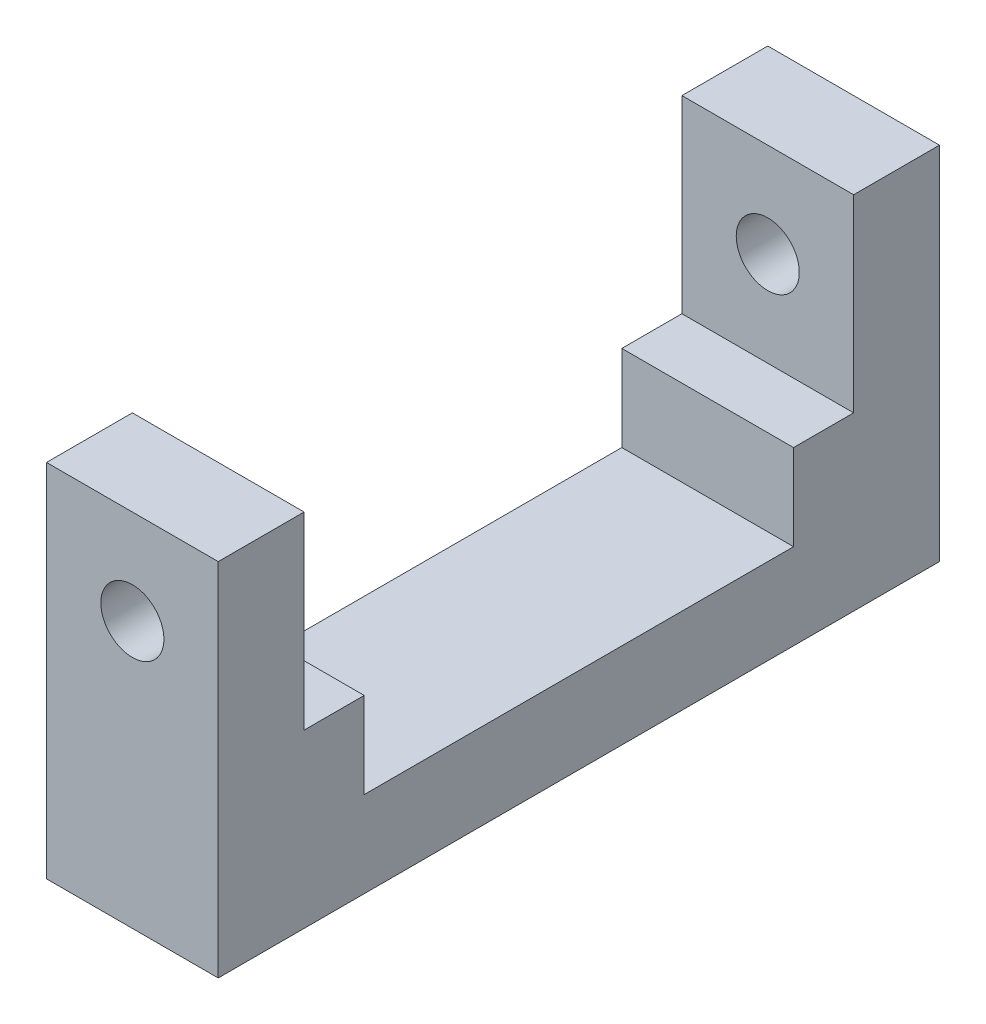
SolidWorks part; units mm, degrees
ref_plane "Front Plane" through (0, 0, 0) normal (0, 0, 1) x (1, 0, 0)
ref_plane "Top Plane" through (0, 0, 0) normal (0, 1, 0) x (1, 0, 0)
ref_plane "Right Plane" through (0, 0, 0) normal (1, 0, 0) x (0, 0, -1)
sketch "Sketch1" plane through (0, 0, 0) normal (1, 0, 0) x (0, 0, -1)
  line L1 (-21, -10.5) -> (21, -10.5)
  line L2 (-21, -10.5) -> (-21, 10.5)
  line L3 (-21, 10.5) -> (21, 10.5)
  line L4 (21, -10.5) -> (21, 10.5)
  line L5 (-21, -10.5) -> (21, 10.5) construction
  line L6 (-21, 10.5) -> (21, -10.5) construction
  line L7 (-16, 10.5) -> (16, 10.5)
  line L8 (-16, 10.5) -> (-16, -5.5)
  line L9 (-16, -5.5) -> (16, -5.5)
  line L10 (16, 10.5) -> (16, -5.5)
  line L11 (12.5, -5.5) -> (-12.5, -5.5)
  line L12 (12.5, -5.5) -> (12.5, -0.5)
  line L13 (12.5, -0.5) -> (-12.5, -0.5)
  line L14 (-12.5, -5.5) -> (-12.5, -0.5)
  line L15 (12.5, -5.5) -> (-12.5, -0.5) construction
  line L16 (12.5, -0.5) -> (-12.5, -5.5) construction
  line L21 (-16, -5.5) -> (-12.5, -5.5)
  line L22 (-16, -5.5) -> (-16, -0.5)
  line L23 (-16, -0.5) -> (-12.5, -0.5)
  line L24 (-12.5, -5.5) -> (-12.5, -0.5)
  line L25 (16, -5.5) -> (12.5, -5.5)
  line L26 (16, -5.5) -> (16, -0.5)
  line L27 (16, -0.5) -> (12.5, -0.5)
  line L28 (12.5, -5.5) -> (12.5, -0.5)
  point P0 (0, 0)
  point P10 (0, -3)
  dimension "D1" = 32
  dimension "D3" = 16
  dimension "D4" = 5
  dimension "D5" = 5
  dimension "D6" = 5
  dimension "D7" = 25
  dimension "D8" = 5
  dimension "D9" = 0
extrude "Boss-Extrude1" add sketch "Sketch1" along normal blind 10 contours L3 L10 L9 L8 L2 L1 L4 | L22 L21 L24 L23 | L26 L25 L28 L27
sketch "Sketch2" plane through (0, 0, -16) normal (0, 0, 1) x (1, 0, 0)
  line L0 (10, 10.5) -> (0, 10.5) construction
  line L2 (10, 10.5) -> (10, -0.5) construction
  circle A0 centre (5, 5) radius 1.8366
  dimension "D1" = 5.5
  dimension "D2" = 5
extrude "Cut-Extrude1" cut sketch "Sketch2" against normal blind 10 and the other way blind 53 contours A0
